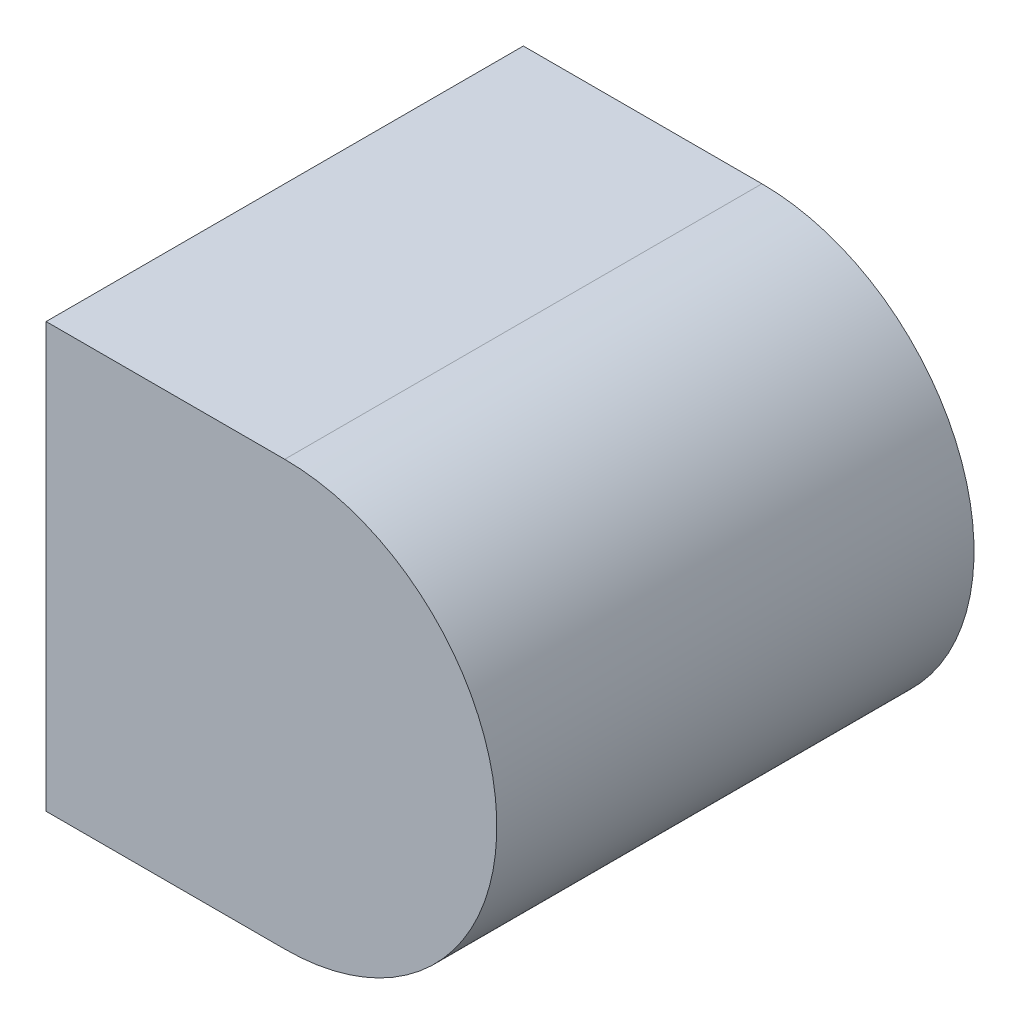
SolidWorks part; units mm, degrees
ref_plane "Front Plane" through (0, 0, 0) normal (0, 0, 1) x (1, 0, 0)
ref_plane "Top Plane" through (0, 0, 0) normal (0, 1, 0) x (1, 0, 0)
ref_plane "Right Plane" through (0, 0, 0) normal (1, 0, 0) x (0, 0, -1)
sketch "Sketch1" plane through (0, 0, 0) normal (0, 0, 1) x (1, 0, 0)
  line L0 (0, -50.8) -> (-57.15, -50.8)
  line L1 (-57.15, -50.8) -> (-57.15, 50.8)
  line L2 (-57.15, 50.8) -> (0, 50.8)
  arc A0 (0, -50.8) -> (0, 50.8) centre (0, 0) ccw
  dimension "D1" = 101.6
  dimension "D2" = 57.15
extrude "Boss-Extrude1" add sketch "Sketch1" along normal blind 114.3
sketch "Sketch2" plane through (0, 0, 114.3) normal (0, 0, 1) x (1, 0, 0)
  circle A0 centre (0, 0) radius 1.27
  dimension "D1" = 2.54
extrude "Boss-Extrude2" add sketch "Sketch2" against normal blind 5.08
